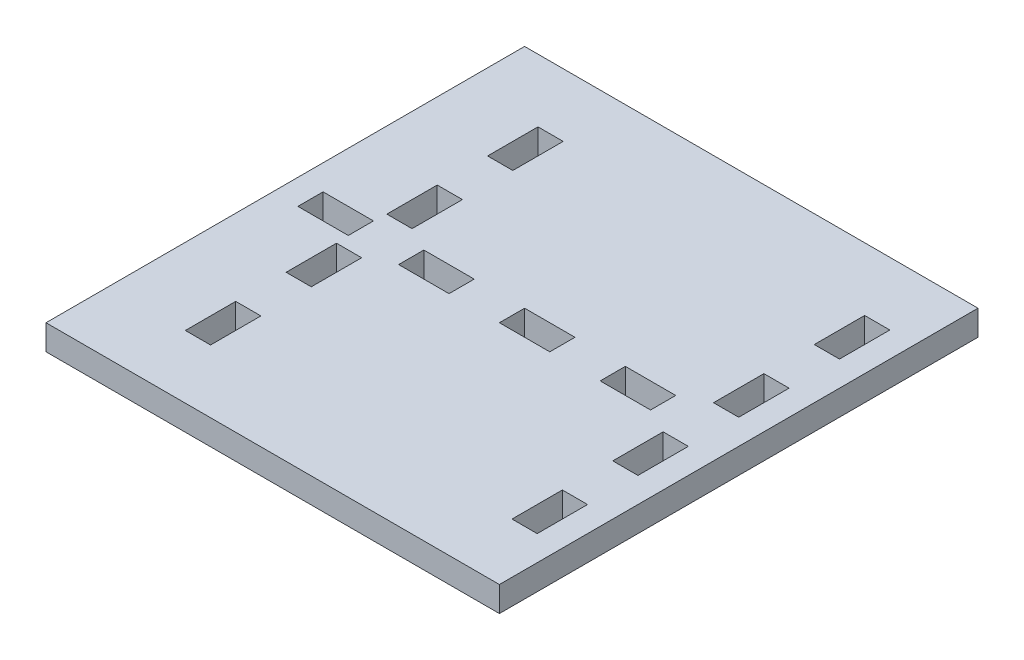
SolidWorks part; units mm, degrees
material "Acrylic (Medium-high impact)"
ref_plane "Front Plane" through (0, 0, 0) normal (0, 0, 1) x (1, 0, 0)
ref_plane "Top Plane" through (0, 0, 0) normal (0, 1, 0) x (1, 0, 0)
ref_plane "Right Plane" through (0, 0, 0) normal (1, 0, 0) x (0, 0, -1)
sketch "Sketch1" plane through (0, 0, 0) normal (0, 1, 0) x (1, 0, 0)
  line L0 (0, 30.1625) -> (57.15, 30.1625) construction
  line L1 (0, 0) -> (57.15, 0)
  line L2 (0, 0) -> (0, 60.325)
  line L3 (0, 60.325) -> (57.15, 60.325)
  line L4 (57.15, 0) -> (57.15, 60.325)
  line L6 (47.625, 31.75) -> (41.275, 31.75)
  line L7 (47.625, 31.75) -> (47.625, 28.575)
  line L8 (47.625, 28.575) -> (41.275, 28.575)
  line L9 (41.275, 31.75) -> (41.275, 28.575)
  line L29 (53.975, 33.3375) -> (50.8, 33.3375)
  line L30 (53.975, 26.9875) -> (50.8, 26.9875)
  line L31 (53.975, 26.9875) -> (53.975, 20.6375)
  line L32 (53.975, 20.6375) -> (50.8, 20.6375)
  line L33 (50.8, 26.9875) -> (50.8, 20.6375)
  line L34 (50.8, 39.6875) -> (50.8, 33.3375)
  line L35 (53.975, 39.6875) -> (53.975, 33.3375)
  line L36 (53.975, 39.6875) -> (50.8, 39.6875)
  line L37 (53.975, 46.0375) -> (50.8, 46.0375)
  line L38 (50.8, 52.3875) -> (50.8, 46.0375)
  line L39 (53.975, 52.3875) -> (53.975, 46.0375)
  line L40 (53.975, 52.3875) -> (50.8, 52.3875)
  line L41 (53.975, 7.9375) -> (50.8, 7.9375)
  line L42 (50.8, 14.2875) -> (50.8, 7.9375)
  line L43 (53.975, 14.2875) -> (53.975, 7.9375)
  line L44 (53.975, 14.2875) -> (50.8, 14.2875)
  line L45 (31.8, 60.325) -> (31.8, 0) construction
  line L46 (9.625, 14.2875) -> (12.8, 14.2875)
  line L47 (9.625, 14.2875) -> (9.625, 7.9375)
  line L48 (12.8, 14.2875) -> (12.8, 7.9375)
  line L49 (9.625, 7.9375) -> (12.8, 7.9375)
  line L50 (9.625, 52.3875) -> (12.8, 52.3875)
  line L51 (9.625, 52.3875) -> (9.625, 46.0375)
  line L52 (12.8, 52.3875) -> (12.8, 46.0375)
  line L53 (9.625, 46.0375) -> (12.8, 46.0375)
  line L54 (9.625, 39.6875) -> (12.8, 39.6875)
  line L55 (9.625, 39.6875) -> (9.625, 33.3375)
  line L56 (12.8, 39.6875) -> (12.8, 33.3375)
  line L57 (12.8, 26.9875) -> (12.8, 20.6375)
  line L58 (9.625, 20.6375) -> (12.8, 20.6375)
  line L59 (9.625, 26.9875) -> (9.625, 20.6375)
  line L60 (9.625, 26.9875) -> (12.8, 26.9875)
  line L61 (9.625, 33.3375) -> (12.8, 33.3375)
  line L62 (34.925, 28.575) -> (28.575, 28.575)
  line L63 (34.925, 31.75) -> (34.925, 28.575)
  line L64 (34.925, 31.75) -> (28.575, 31.75)
  line L65 (28.575, 31.75) -> (28.575, 28.575)
  line L66 (22.225, 28.575) -> (15.875, 28.575)
  line L67 (22.225, 31.75) -> (22.225, 28.575)
  line L68 (22.225, 31.75) -> (15.875, 31.75)
  line L69 (15.875, 31.75) -> (15.875, 28.575)
  line L70 (9.525, 28.575) -> (3.175, 28.575)
  line L71 (9.525, 31.75) -> (9.525, 28.575)
  line L72 (9.525, 31.75) -> (3.175, 31.75)
  line L73 (3.175, 31.75) -> (3.175, 28.575)
  line L74 (-3.175, 28.575) -> (-9.525, 28.575) [skipped]
  line L75 (-3.175, 31.75) -> (-3.175, 28.575) [skipped]
  line L76 (-3.175, 31.75) -> (-9.525, 31.75) [skipped]
  line L77 (-9.525, 31.75) -> (-9.525, 28.575) [skipped]
  line L78 (-15.875, 28.575) -> (-22.225, 28.575) [skipped]
  line L79 (-15.875, 31.75) -> (-15.875, 28.575) [skipped]
  line L80 (-15.875, 31.75) -> (-22.225, 31.75) [skipped]
  line L81 (-22.225, 31.75) -> (-22.225, 28.575) [skipped]
  dimension "D1" = 57.15
  dimension "D2" = 60.325
  dimension "D3" = 3.175
  dimension "D4" = 1.5875
  dimension "D5" = 6.35
  dimension "D6" = 9.525
  dimension "D8" = 6.35
  dimension "D9" = 3.175
  dimension "D10" = 3.175
  dimension "D11" = 6.35
  dimension "D12" = 3.175
  dimension "D15" = 6.35
  dimension "D16" = 6.35
  dimension "D17" = 19
  dimension "D7" = 4
  dimension "D13" = 3
  dimension "D14" = 2
extrude "Boss-Extrude1" add sketch "Sketch1" along normal blind 3.175
